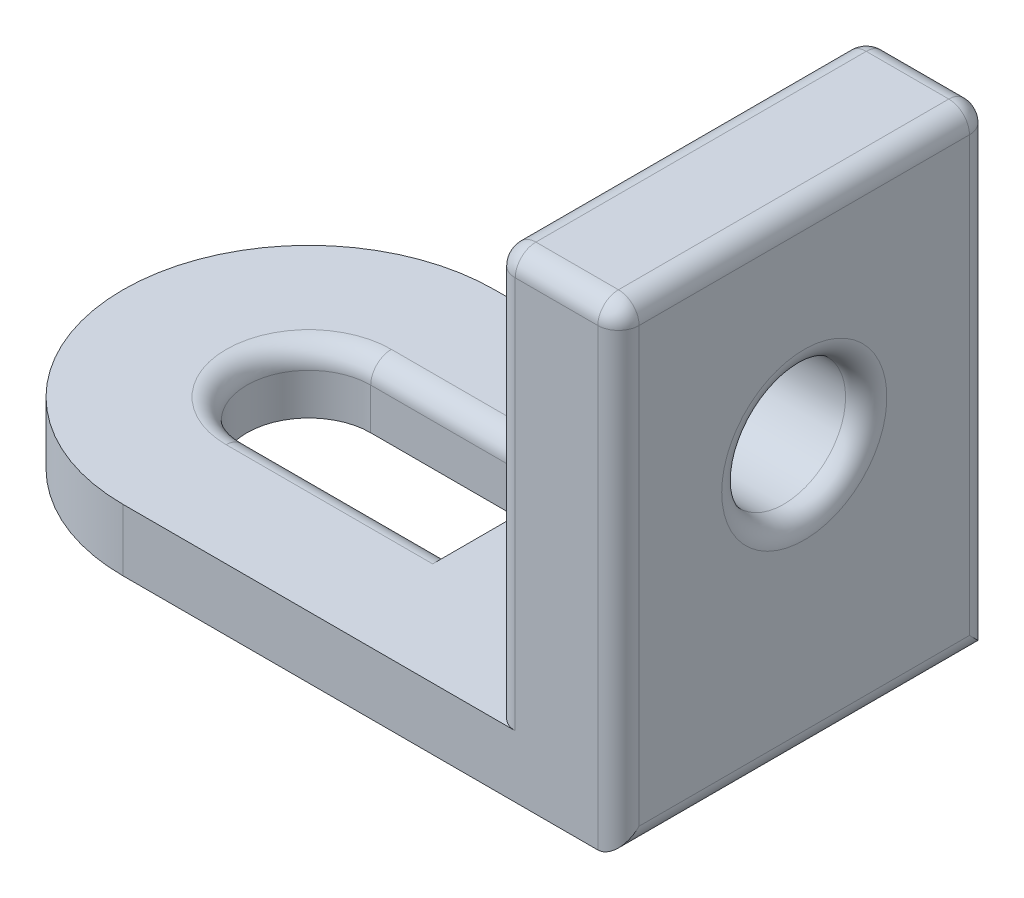
SolidWorks part; units mm, degrees
ref_plane "Front Plane" through (0, 0, 0) normal (0, 0, 1) x (1, 0, 0)
ref_plane "Top Plane" through (0, 0, 0) normal (0, 1, 0) x (1, 0, 0)
ref_plane "Right Plane" through (0, 0, 0) normal (1, 0, 0) x (0, 0, -1)
sketch "Sketch1" plane through (0, 0, 0) normal (0, 1, 0) x (1, 0, 0)
  line L1 (0, 9) -> (24, 9)
  line L3 (0, -9) -> (24, -9)
  line L4 (24, 9) -> (24, -9)
  line L5 (-8.427, 3.1601) -> (24, -9) construction
  line L6 (-8.427, -3.1601) -> (24, 9) construction
  arc A0 (0, 9) -> (0, -9) centre (0, 0) ccw
  dimension "D1" = 18
  dimension "D2" = 24
  dimension "D3" = 18
extrude "Boss-Extrude1" add sketch "Sketch1" along normal blind 3
sketch "Sketch2" plane through (0, 3, 0) normal (0, 1, 0) x (1, 0, 0)
  line L0 (0, 0) -> (24, 0) construction
  line L1 (24, -9) -> (24, 9) construction
  line L4 (0, 3) -> (10, 3)
  line L6 (0, -3) -> (10, -3)
  line L7 (10, 3) -> (10, -3)
  arc A0 (0, 3) -> (0, -3) centre (0, 0) ccw
  dimension "D1" = 10
extrude "Cut-Extrude1" cut sketch "Sketch2" against normal up to surface (3 mm away) up to face at (9.75, 0, 0)
sketch "Sketch3" plane through (0, 3, 0) normal (0, 1, 0) x (1, 0, 0)
  line L0 (0, -9) -> (24, -9) construction
  line L1 (24, 9) -> (18, 9)
  line L2 (24, 9) -> (24, -9)
  line L3 (24, -9) -> (18, -9)
  line L4 (18, 9) -> (18, -9)
  dimension "D1" = 6
extrude "Boss-Extrude2" add sketch "Sketch3" along normal blind 20
fillet "Fillet1" radius 1 3 edges at (24, 11.5, 9) (24, 11.5, -9) (24, 0, 0)
fillet "Fillet3" radius 1 8 edges at (23.7071, 23, 8.7071) (23.7071, 23, -8.7071) (18, 23, 0) (20.5, 23, -9) (20.5, 23, 9) (24, 23, 0)
fillet "Fillet6" radius 1 3 edges at (-3, 3, 0) (5, 3, -3) (5, 3, 3)
sketch "Sketch4" plane through (24, 0, 0) normal (1, 0, 0) x (0, 0, -1)
  line L0 (-2.8637, 3) -> (4.753, 3) construction
  line L3 (0, 23) -> (0, 0) construction
  line L4 (-8, 23) -> (8, 23) construction
  line L5 (9, 0) -> (-9, 0) construction
  circle A0 centre (0, 13) radius 3
  dimension "D1" = 3
  dimension "D2" = 10
extrude "Cut-Extrude2" cut sketch "Sketch4" against normal through all
fillet "Fillet7" radius 1 1 edges at (24, 13, -3)
